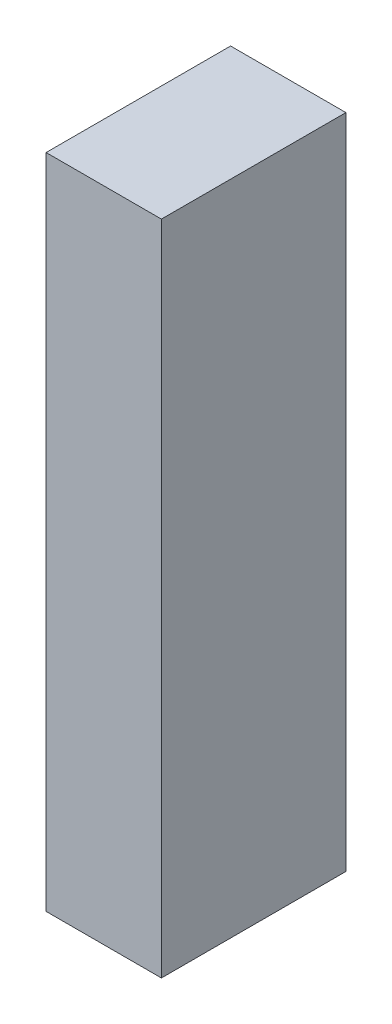
SolidWorks part; units mm, degrees
ref_plane "Front Plane" through (0, 0, 0) normal (0, 0, 1) x (1, 0, 0)
ref_plane "Top Plane" through (0, 0, 0) normal (0, 1, 0) x (1, 0, 0)
ref_plane "Right Plane" through (0, 0, 0) normal (1, 0, 0) x (0, 0, -1)
other "Configuration Table"
sketch "Sketch1" plane through (0, 0, 0) normal (0, 0, 1) x (1, 0, 0)
  line L1 (300, 1120) -> (400, 1120)
  line L2 (300, 1120) -> (300, 1690)
  line L3 (300, 1690) -> (400, 1690)
  line L4 (400, 1120) -> (400, 1690)
extrude "OVEN_firin_buhar_kanali_1" add sketch "Sketch1" against normal blind 160 from offset 600 separate body
